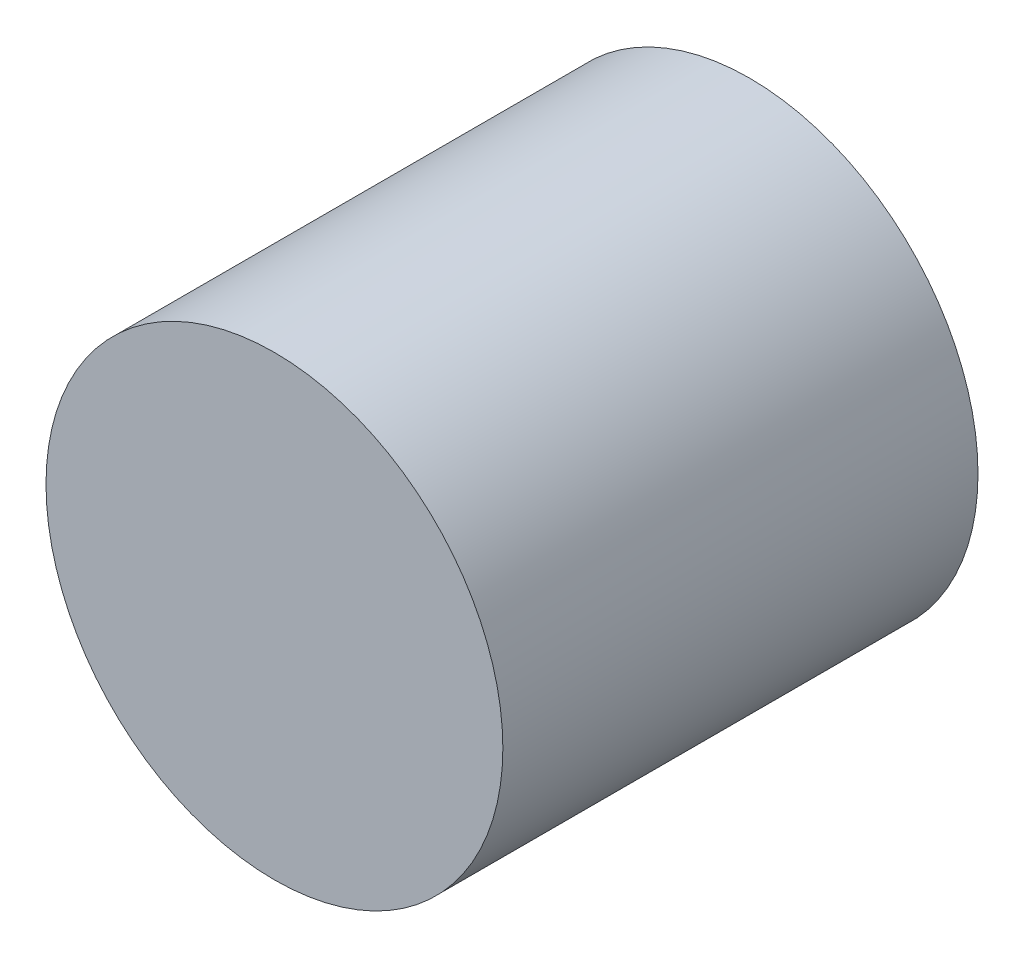
SolidWorks part; units mm, degrees
ref_plane "Front Plane" through (0, 0, 0) normal (0, 0, 1) x (1, 0, 0)
ref_plane "Top Plane" through (0, 0, 0) normal (0, 1, 0) x (1, 0, 0)
ref_plane "Right Plane" through (0, 0, 0) normal (1, 0, 0) x (0, 0, -1)
sketch "Sketch1" plane through (0, 0, 0) normal (0, 0, 1) x (1, 0, 0)
  circle A0 centre (0, 0) radius 4.7625
  dimension "D1" = 9.525
extrude "Boss-Extrude1" add sketch "Sketch1" along normal blind 9.906
